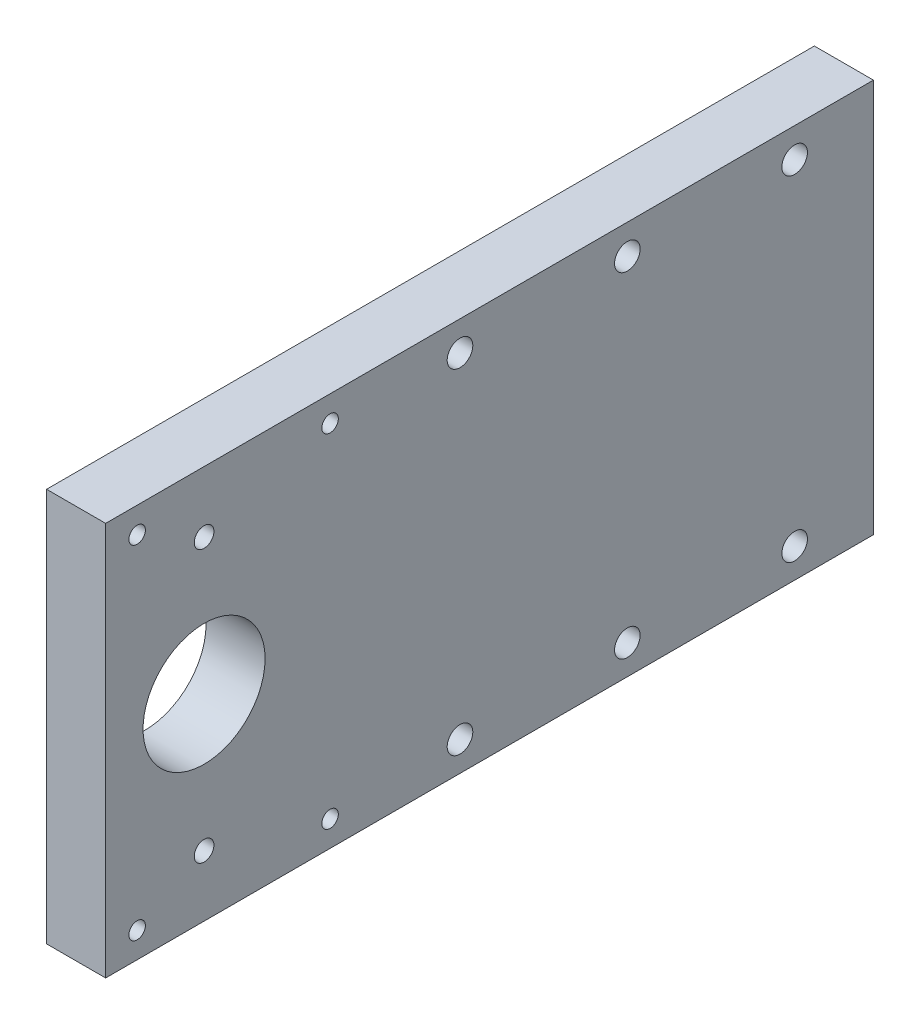
SolidWorks part; units mm, degrees
ref_plane "Front" through (0, 0, 0) normal (0, 0, 1) x (1, 0, 0)
ref_plane "Top" through (0, 0, 0) normal (0, 1, 0) x (1, 0, 0)
ref_plane "Right" through (0, 0, 0) normal (1, 0, 0) x (0, 0, -1)
sketch "Sketch11" plane through (0, 0, 0) normal (1, 0, 0) x (0, 0, -1)
  line L0 (7.6025, 0) -> (-207.2639, 0) construction
  line L1 (0, -50) -> (-195, -50)
  line L2 (0, -50) -> (0, 50)
  line L3 (0, 50) -> (-195, 50)
  line L4 (-195, -50) -> (-195, 50)
  dimension "D1" = 100
  dimension "D2" = 195
extrude "Boss-Extrude2" add sketch "Sketch11" against normal blind 15
sketch "Sketch2" plane through (0, 0, 0) normal (1, 0, 0) x (0, 0, -1)
  line L1 (0, -50) -> (0, 50) construction
  circle A0 centre (-170, 0) radius 15.5
  dimension "D1" = 170
  dimension "D2" = 31
extrude "Cut-Extrude1" cut sketch "Sketch2" against normal through all
hole_wizard "M6 Tapped Hole1" positions "Sketch4" profile "Sketch3" tap size "M6" standard "ISO"
sketch "Sketch4" plane through (-11.9816, -34.6586, 0) normal (0, 0, -1) x (-1, 0, 0)
  line L0 (-11.9816, 34.6586) -> (3.0184, 34.6586) construction
  line L4 (3.0184, -15.3414) -> (3.0184, 84.6586) construction
  line L5 (-11.9816, -15.3414) -> (-11.9816, 84.6586) construction
  point P0 (-4.4816, -0.3414)
  point P1 (-4.4816, 69.6586)
  dimension "D1" = 70
  dimension "D2" = 7.5
sketch "Sketch3" plane through (-7.5, -35, 0) normal (1, 0, 0) x (0, 1, 0)
  line L0 (0, 0) -> (0, 13.5022)
  line L1 (0, 13.5022) -> (2.5, 12)
  line L2 (2.5, 12) -> (2.5, 0)
  line L5 (2.5, 0) -> (0, 0)
  line L10 (0, 13.5022) -> (-2.5, 12) construction
  line L11 (0, -6.35) -> (0, 107.95) construction
  dimension "Tap Drill Dia." = 5
  dimension "Tap Drill Depth" = 12
  dimension "Drill Angle" = 118
cosmetic thread "Hole Thread1" parameters "D1"=9, "D2"=6
cosmetic thread "Hole Thread2" parameters "D1"=9, "D2"=6
hole_wizard "Ø6.5 (6.5) Diameter Hole1" positions "Sketch6" profile "Sketch5" hole size "Ø6.5" standard "ISO" end condition through all
sketch "Sketch6" plane through (0, -7.3628, 24.8744) normal (1, 0, 0) x (0, 0, -1)
  line L0 (24.8744, 7.3628) -> (-170.1256, 7.3628) construction
  line L4 (-170.1256, 57.3628) -> (-170.1256, -42.6372) construction
  line L5 (24.8744, -42.6372) -> (24.8744, 57.3628) construction
  point P0 (-80.1256, -35.1372)
  point P1 (-37.6256, -35.1372)
  point P3 (4.8744, -35.1372)
  point P5 (-80.1256, 49.8628)
  point P7 (-37.6256, 49.8628)
  point P9 (4.8744, 49.8628)
  dimension "D1" = 85
  dimension "D2" = 20
  dimension "D3" = 42.5
  dimension "D4" = 42.5
sketch "Sketch5" plane through (0, -42.5, 105) normal (0, 1, 0) x (0, 0, -1)
  line L0 (0, 0) -> (0, 15)
  line L1 (0, 15) -> (3.25, 15)
  line L2 (3.25, 15) -> (3.25, 0)
  line L5 (3.25, 0) -> (0, 0)
  line L11 (0, -6.35) -> (0, 107.95) construction
  dimension "Thru Hole Dia." = 6.5
  dimension "Thru Hole Depth" = 15
hole_wizard "M5 Tapped Hole1" positions "Sketch8" profile "Sketch7" tap size "M5" standard "ISO"
sketch "Sketch8" plane through (0, -36.2912, 74.0469) normal (-1, 0, 0) x (0, 0, 1)
  line L0 (-74.0469, 36.2912) -> (120.9531, 36.2912) construction
  line L4 (120.9531, 86.2912) -> (120.9531, -13.7088) construction
  line L5 (-74.0469, -13.7088) -> (-74.0469, 86.2912) construction
  point P0 (63.9531, -7.2088)
  point P1 (112.9531, -7.2088)
  point P3 (112.9531, 79.7912)
  point P5 (63.9531, 79.7912)
  dimension "D1" = 87
  dimension "D2" = 138
  dimension "D3" = 49
sketch "Sketch7" plane through (0, -43.5, 138) normal (0, 1, 0) x (0, 0, -1)
  line L0 (0, 0) -> (0, 13.2618)
  line L1 (0, 13.2618) -> (2.1, 12)
  line L2 (2.1, 12) -> (2.1, 0)
  line L5 (2.1, 0) -> (0, 0)
  line L10 (0, 13.2618) -> (-2.1, 12) construction
  line L11 (0, -6.35) -> (0, 107.95) construction
  dimension "Tap Drill Dia." = 4.2
  dimension "Tap Drill Depth" = 12
  dimension "Drill Angle" = 118
cosmetic thread "Hole Thread3" parameters "D1"=10, "D2"=5
cosmetic thread "Hole Thread4" parameters "D1"=10, "D2"=5
cosmetic thread "Hole Thread5" parameters "D1"=10, "D2"=5
cosmetic thread "Hole Thread6" parameters "D1"=10, "D2"=5
hole_wizard "M6 Tapped Hole2" positions "Sketch10" profile "Sketch9" tap size "M6" standard "ISO" end condition through all
sketch "Sketch10" plane through (0, -42.1048, 47.9632) normal (1, 0, 0) x (0, 0, -1)
  line L0 (47.9632, 42.1048) -> (-147.0368, 42.1048) construction
  line L4 (-147.0368, 92.1048) -> (-147.0368, -7.8952) construction
  line L5 (47.9632, -7.8952) -> (47.9632, 92.1048) construction
  point P0 (-122.0368, 7.6048)
  point P1 (-122.0368, 76.6048)
  dimension "D1" = 69
  dimension "D2" = 170
sketch "Sketch9" plane through (0, -34.5, 170) normal (0, 1, 0) x (0, 0, -1)
  line L0 (0, 0) -> (0, 15)
  line L1 (0, 15) -> (2.5, 15)
  line L2 (2.5, 15) -> (2.5, 0)
  line L5 (2.5, 0) -> (0, 0)
  line L11 (0, -6.35) -> (0, 107.95) construction
  dimension "Thru Tap Drill Dia." = 5
  dimension "Thru Tap Drill Depth" = 15
cosmetic thread "Hole Thread7" parameters "D2"=6
cosmetic thread "Hole Thread8" parameters "D2"=6
